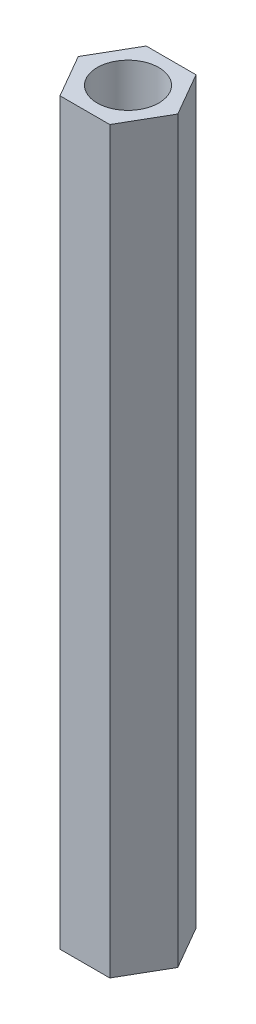
SolidWorks part; units mm, degrees
ref_plane "前视基准面" through (0, 0, 0) normal (0, 0, 1) x (1, 0, 0)
ref_plane "上视基准面" through (0, 0, 0) normal (0, 1, 0) x (1, 0, 0)
ref_plane "右视基准面" through (0, 0, 0) normal (1, 0, 0) x (0, 0, -1)
other "Configuration Table"
sketch "草图1" plane through (0, 0, 0) normal (0, 1, 0) x (1, 0, 0)
  line L1 (2.0207, 3.5) -> (-2.0207, 3.5)
  line L2 (-2.0207, 3.5) -> (-4.0415, 0)
  line L3 (-4.0415, 0) -> (-2.0207, -3.5)
  line L4 (-2.0207, -3.5) -> (2.0207, -3.5)
  line L5 (2.0207, -3.5) -> (4.0415, 0)
  line L6 (4.0415, 0) -> (2.0207, 3.5)
  circle A0 centre (0, 0) radius 3.5 construction
  circle A1 centre (0, 0) radius 2.5
  dimension "D1" = 7
extrude "凸台-拉伸1" add sketch "草图1" along normal blind 60
